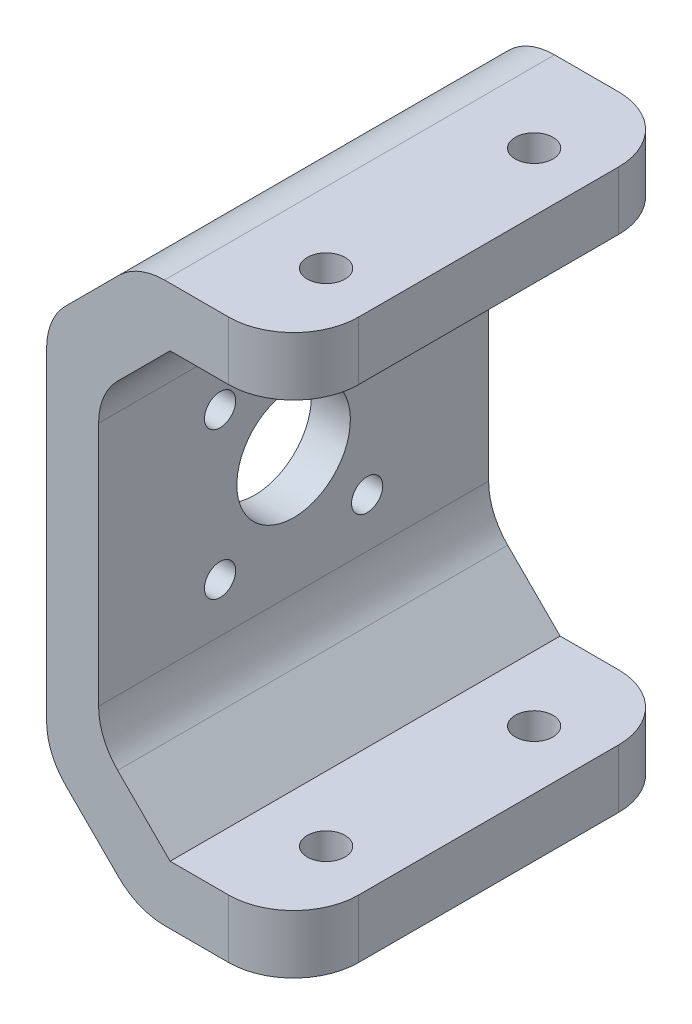
SolidWorks part; units mm, degrees
material "Onyx w/ CF"
ref_plane "Front Plane" through (0, 0, 0) normal (0, 0, 1) x (1, 0, 0)
ref_plane "Top Plane" through (0, 0, 0) normal (0, 1, 0) x (1, 0, 0)
ref_plane "Right Plane" through (0, 0, 0) normal (1, 0, 0) x (0, 0, -1)
other "Center of Mass"
sketch "Sketch2" plane through (0, 0, 0) normal (0, 0, 1) x (1, 0, 0)
  line L0 (0, 21.5) -> (0, -21.5)
  line L1 (0, -21.5) -> (19, -21.5)
  line L2 (19, -21.5) -> (19, -17)
  line L3 (19, -17) -> (4, -17)
  line L4 (4, -17) -> (4, 17)
  line L5 (4, 17) -> (19, 17)
  line L6 (19, 17) -> (19, 21.5)
  line L7 (19, 21.5) -> (0, 21.5)
  point P4 (0, 0)
  dimension "D1" = 4.5
  dimension "D2" = 4
  dimension "D3" = 15
  dimension "D4" = 34
extrude "Boss-Extrude1" add sketch "Sketch2" along normal mid plane 30
hole_wizard "M2.5 Clearance Hole1" positions "Sketch6" profile "Sketch7" hole size "M2.5" standard "ANSI Metric" end condition through all
sketch "Sketch6" plane through (0, -21.5, 0) normal (0, -1, 0) x (-1, 0, 0)
  line L0 (-14.5, 8) -> (-14.5, -8)
  line L2 (-19, -15) -> (-19, 15) construction
  point P0 (-14.5, -8)
  point P2 (-14.5, 8)
  point P15 (-14.5, 0)
  dimension "D1" = 4.5
  dimension "D2" = 16
sketch "Sketch7" plane through (14.5, -21.5, 8) normal (1, 0, 0) x (0, 0, -1)
  line L0 (0, 0) -> (0, 43)
  line L1 (0, 43) -> (1.45, 43)
  line L2 (1.45, 43) -> (1.45, 0)
  line L5 (1.45, 0) -> (0, 0)
  line L11 (0, -6.35) -> (0, 107.95) construction
  dimension "Thru Hole Dia." = 2.9
  dimension "Thru Hole Depth" = 43
sketch "Sketch3" plane through (4, 0, 0) normal (1, 0, 0) x (0, 0, -1)
  circle A0 centre (0, 0) radius 4.3656
  dimension "D1" = 8.7312
extrude "Cut-Extrude1" cut sketch "Sketch3" against normal through all both and the other way through all
hole_wizard "M2 Clearance Hole1" positions "Sketch4" profile "Sketch5" hole size "M2" standard "ANSI Metric" end condition through all
sketch "Sketch4" plane through (0, 0, 0) normal (-1, 0, 0) x (0, 0, 1)
  line L1 (5.6569, 5.6569) -> (-5.6569, 5.6569)
  line L2 (5.6569, 5.6569) -> (5.6569, -5.6569)
  line L3 (5.6569, -5.6569) -> (-5.6569, -5.6569)
  line L4 (-5.6569, 5.6569) -> (-5.6569, -5.6569)
  line L5 (5.6569, 5.6569) -> (-5.6569, -5.6569) construction
  line L6 (5.6569, -5.6569) -> (-5.6569, 5.6569) construction
  point P0 (5.6569, 5.6569)
  point P2 (5.6569, -5.6569)
  point P4 (-5.6569, -5.6569)
  point P6 (-5.6569, 5.6569)
  point P9 (0, 0)
  dimension "D1" = 11.3137
sketch "Sketch5" plane through (0, 5.6569, 5.6569) normal (0, 1, 0) x (0, 0, 1)
  line L0 (0, 0) -> (0, 19)
  line L1 (0, 19) -> (1.2, 19)
  line L2 (1.2, 19) -> (1.2, 0)
  line L5 (1.2, 0) -> (0, 0)
  line L11 (0, -6.35) -> (0, 107.95) construction
  dimension "Thru Hole Dia." = 2.4
  dimension "Thru Hole Depth" = 19
sketch "Sketch10" plane through (0, 0, 0) normal (-1, 0, 0) x (0, 0, 1)
  circle A0 centre (0, 0) radius 11.5
  dimension "D1" = 23
extrude "Cut-Extrude3" cut sketch "Sketch10" against normal blind 1
chamfer "Chamfer1" distance 5.5 angle 45 2 edges at (4, -17, 0) (4, 17, 0)
chamfer "Chamfer2" distance 7 angle 45 2 edges at (0, 21.5, 0) (0, -21.5, 0)
fillet "Fillet1" radius 5 4 edges at (19, -19.25, 15) (19, -19.25, -15) (19, 19.25, -15) (19, 19.25, 15)
fillet "Fillet2" radius 5 6 edges at (7, -21.5, 0) (0, -14.5, 0) (4, -11.5, 0) (4, 11.5, 0) (7, 21.5, 0) (0, 14.5, 0)
